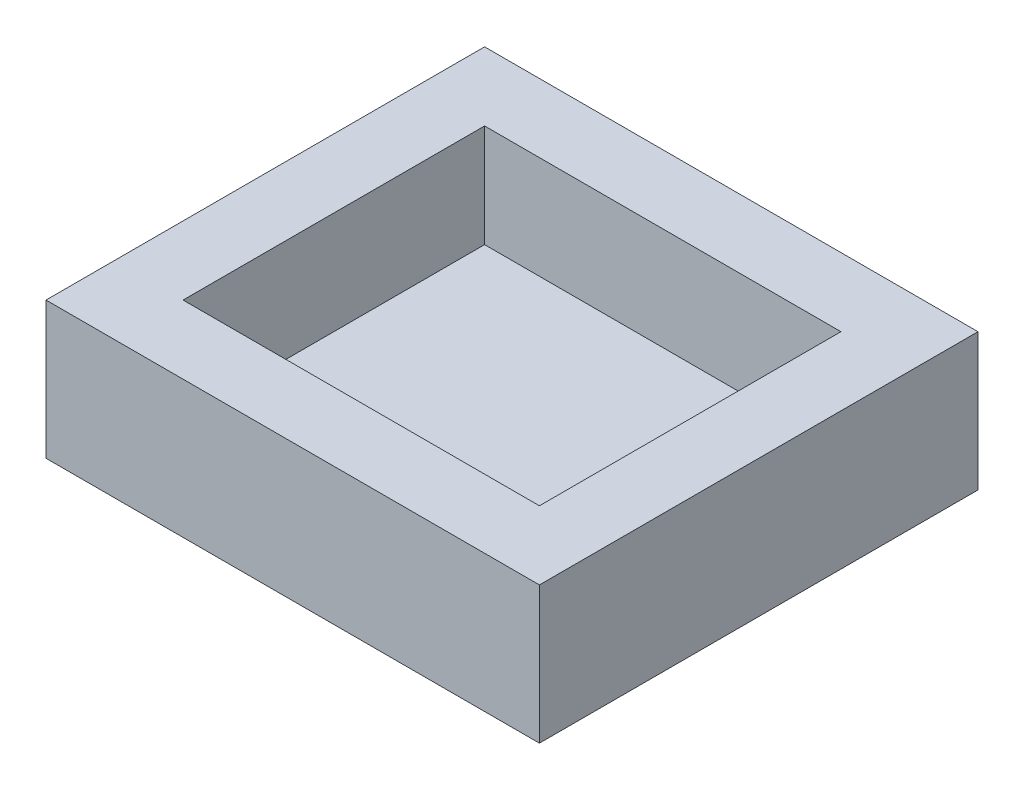
SolidWorks part; units mm, degrees
ref_plane "Front Plane" through (0, 0, 0) normal (0, 0, 1) x (1, 0, 0)
ref_plane "Top Plane" through (0, 0, 0) normal (0, 1, 0) x (1, 0, 0)
ref_plane "Right Plane" through (0, 0, 0) normal (1, 0, 0) x (0, 0, -1)
sketch "Sketch2" plane through (0, 0, 0) normal (0, 1, 0) x (1, 0, 0)
  line L1 (-22.86, -20.32) -> (22.86, -20.32)
  line L2 (-22.86, -20.32) -> (-22.86, 20.32)
  line L3 (-22.86, 20.32) -> (22.86, 20.32)
  line L4 (22.86, -20.32) -> (22.86, 20.32)
  line L5 (-22.86, -20.32) -> (22.86, 20.32) construction
  line L6 (-22.86, 20.32) -> (22.86, -20.32) construction
  point P0 (0, 0)
  dimension "D1" = 40.64
  dimension "D2" = 45.72
extrude "Boss-Extrude1" add sketch "Sketch2" along normal blind 12.7
sketch "Sketch3" plane through (0, 12.7, 0) normal (0, 1, 0) x (1, 0, 0)
  line L0 (22.86, 20.32) -> (-22.86, 20.32) construction
  line L1 (-16.51, -13.97) -> (16.51, -13.97)
  line L2 (-16.51, -13.97) -> (-16.51, 13.97)
  line L3 (-16.51, 13.97) -> (16.51, 13.97)
  line L4 (16.51, -13.97) -> (16.51, 13.97)
  line L5 (-16.51, -13.97) -> (16.51, 13.97) construction
  line L6 (-16.51, 13.97) -> (16.51, -13.97) construction
  line L7 (-22.86, 20.32) -> (-22.86, -20.32) construction
  point P0 (0, 0)
  dimension "D1" = 6.35
  dimension "D2" = 6.35
extrude "Cut-Extrude1" cut sketch "Sketch3" against normal blind 9.525
